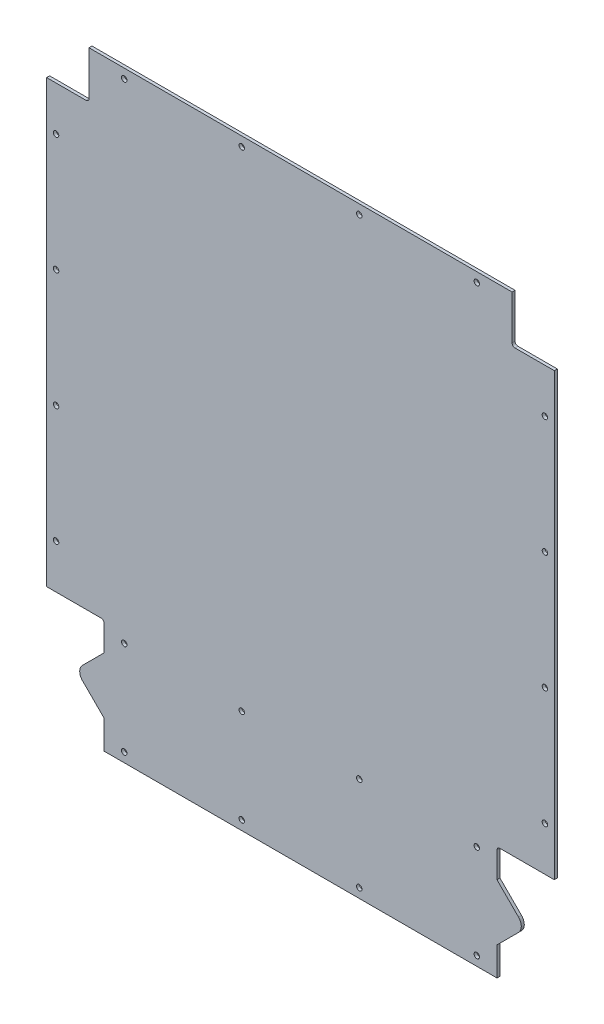
SolidWorks part; units mm, degrees
ref_plane "Front Plane" through (0, 0, 0) normal (0, 0, 1) x (1, 0, 0)
ref_plane "Top Plane" through (0, 0, 0) normal (0, 1, 0) x (1, 0, 0)
ref_plane "Right Plane" through (0, 0, 0) normal (1, 0, 0) x (0, 0, -1)
sketch "Sketch2" plane through (0, 0, 0) normal (0, 0, 1) x (1, 0, 0)
  line L1 (0, 0) -> (540, 0)
  line L2 (0, 0) -> (0, 640)
  line L3 (0, 640) -> (540, 640)
  line L4 (540, 0) -> (540, 640)
  dimension "D1" = 640
  dimension "D2" = 540
extrude "Boss-Extrude1" add sketch "Sketch2" along normal blind 3.175
sketch "Sketch3" plane through (0, 0, 3.175) normal (0, 0, 1) x (1, 0, 0)
  line L1 (0, 640) -> (0, 0) construction
  line L2 (0, 590) -> (45, 590)
  line L3 (540, 640) -> (0, 640) construction
  line L4 (0, 590) -> (0, 640)
  line L5 (0, 0) -> (540, 0) construction
  line L6 (270, 0) -> (270, 640) construction
  line L8 (45, 590) -> (45, 640)
  line L9 (0, 640) -> (45, 640)
  line L10 (0, 121) -> (61, 121)
  line L11 (61, 121) -> (61, 90.5)
  line L12 (61, 90.5) -> (31, 60.5)
  line L13 (31, 60.5) -> (61, 30.5)
  line L14 (61, 30.5) -> (61, 0)
  line L15 (61, 0) -> (0, 0)
  line L16 (0, 0) -> (0, 121)
  line L17 (540, 0) -> (540, 121)
  line L18 (479, 0) -> (540, 0)
  line L19 (479, 30.5) -> (479, 0)
  line L20 (509, 60.5) -> (479, 30.5)
  line L21 (479, 90.5) -> (509, 60.5)
  line L22 (479, 121) -> (479, 90.5)
  line L23 (540, 121) -> (479, 121)
  line L28 (540, 640) -> (495, 640)
  line L29 (495, 590) -> (495, 640)
  line L30 (540, 590) -> (540, 640)
  line L31 (540, 590) -> (495, 590)
  dimension "D1" = 50
  dimension "D2" = 121
  dimension "D3" = 31
  dimension "D4" = 61
  dimension "D5" = 45
extrude "Cut-Extrude1" cut sketch "Sketch3" against normal through all
fillet "Fillet1" radius 10 2 edges at (509, 60.5, 1.5875) (31, 60.5, 1.5875)
fillet "Fillet2" radius 3.175 4 edges at (45, 590, 1.5875) (495, 590, 1.5875) (479, 121, 1.5875) (61, 121, 1.5875)
hole_wizard "M5 Clearance Hole1" positions "3DSketch1" profile "Sketch4" hole size "M5" standard "ANSI Metric" end condition through all
sketch3d "3DSketch1"
  line L0 (82.5, 110, 3.175) -> (82.5, 10, 3.175) construction
  line L2 (61, 0, 3.175) -> (479, 0, 3.175) construction
  line L3 (61, 0, 3.175) -> (61, 30.5, 3.175) construction
  line L4 (82.5, 630, 3.175) -> (82.5, 110, 3.175) construction
  line L6 (495, 640, 3.175) -> (45, 640, 3.175) construction
  point P0 (82.5, 10, 3.175)
  point P2 (82.5, 110, 3.175)
  point P12 (82.5, 630, 3.175)
  dimension "D1" = 100
  dimension "D2" = 10
  dimension "D3" = 21.5
  dimension "D4" = 10
sketch "Sketch4" plane through (82.5, 10, 3.175) normal (1, 0, 0) x (0, -1, 0)
  line L0 (0, 0) -> (0, 3.175)
  line L1 (0, 3.175) -> (2.9, 3.175)
  line L2 (2.9, 3.175) -> (2.9, 0)
  line L5 (2.9, 0) -> (0, 0)
  line L11 (0, -6.35) -> (0, 107.95) construction
  dimension "Thru Hole Dia." = 5.8
  dimension "Thru Hole Depth" = 3.175
pattern_linear "LPattern1" count 4 spacing 125 along (1, 0, 0) of "M5 Clearance Hole1"
hole_wizard "M5 Clearance Hole2" positions "3DSketch2" profile "Sketch5" hole size "M5" standard "ANSI Metric" end condition through all
sketch3d "3DSketch2"
  line L0 (10, 168, 3.175) -> (0, 168, 3.175) construction
  line L1 (0, 590, 3.175) -> (0, 121, 3.175) construction
  line L3 (530, 168, 3.175) -> (540, 168, 3.175) construction
  line L4 (540, 121, 3.175) -> (540, 590, 3.175) construction
  line L6 (57.825, 121, 3.175) -> (0, 121, 3.175) construction
  point P0 (10, 168, 3.175)
  point P2 (530, 168, 3.175)
  dimension "D1" = 10
  dimension "D2" = 47
sketch "Sketch5" plane through (10, 168, 3.175) normal (1, 0, 0) x (0, -1, 0)
  line L0 (0, 0) -> (0, 3.175)
  line L1 (0, 3.175) -> (2.9, 3.175)
  line L2 (2.9, 3.175) -> (2.9, 0)
  line L5 (2.9, 0) -> (0, 0)
  line L11 (0, -6.35) -> (0, 107.95) construction
  dimension "Thru Hole Dia." = 5.8
  dimension "Thru Hole Depth" = 3.175
pattern_linear "LPattern2" count 4 spacing 125 along (0, 1, 0) of "M5 Clearance Hole2"
